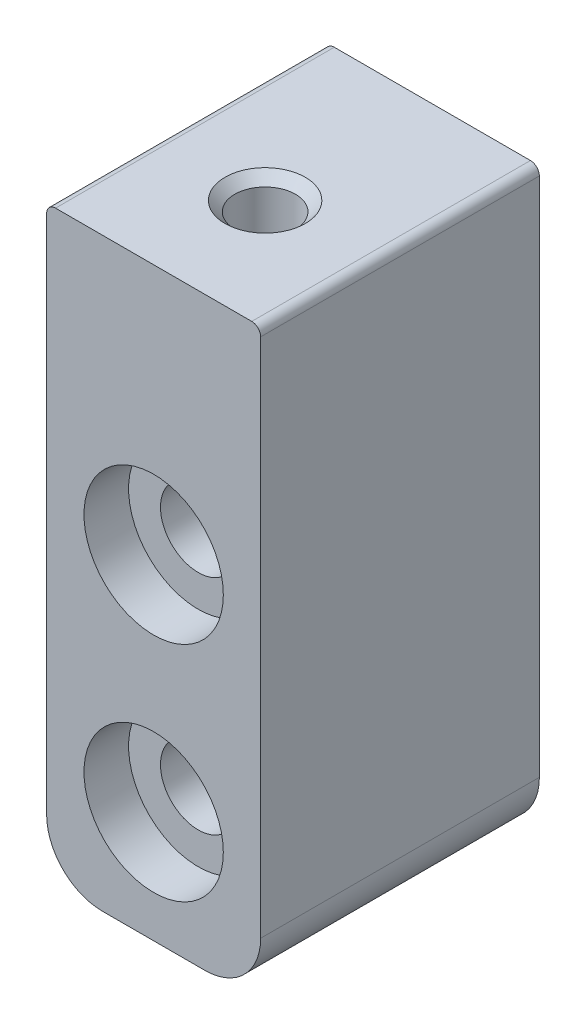
SolidWorks part; units mm, degrees
ref_plane "Front Plane" through (0, 0, 0) normal (0, 0, 1) x (1, 0, 0)
ref_plane "Top Plane" through (0, 0, 0) normal (0, 1, 0) x (1, 0, 0)
ref_plane "Right Plane" through (0, 0, 0) normal (1, 0, 0) x (0, 0, -1)
sketch "Sketch1" plane through (0, 0, 0) normal (1, 0, 0) x (0, 0, -1)
  line L1 (0, 0) -> (-15.875, 0)
  line L2 (0, 0) -> (0, -33.3502)
  line L3 (0, -33.3502) -> (-15.875, -33.3502)
  line L4 (-15.875, 0) -> (-15.875, -33.3502)
  dimension "D1" = 15.875
  dimension "D2" = 33.3502
extrude "Boss-Extrude1" add sketch "Sketch1" along normal mid plane 12.192
hole_wizard "CBORE for #8 Socket Head Cap Screw1" positions "Sketch3" profile "Sketch2" counterbore size "#8" standard "Ansi Inch" end condition through all
sketch "Sketch3" plane through (0, 0, 15.875) normal (0, 0, 1) x (1, 0, 0)
  point P0 (0, -14.3002)
  point P1 (0, -27.0002)
  dimension "D1" = 14.3002
  dimension "D2" = 12.7
sketch "Sketch2" plane through (0, -14.3002, 15.875) normal (1, 0, 0) x (0, -1, 0)
  line L0 (0, 0) -> (0, 15.875)
  line L1 (0, 15.875) -> (2.1526, 15.875)
  line L3 (2.1526, 15.875) -> (2.1527, 2.54)
  line L4 (2.1527, 2.54) -> (3.9688, 2.54)
  line L5 (3.9688, 2.54) -> (3.9687, 0)
  line L7 (3.9687, 0) -> (0, 0)
  line L11 (0, -6.35) -> (0, 107.95) construction
  dimension "Thru Hole Dia." = 4.3053
  dimension "Thru Hole Depth" = 15.875
  dimension "C'Bore Dia." = 7.9375
  dimension "C'Bore Depth" = 2.54
hole_wizard "#8-32 Tapped Hole1" positions "Sketch5" profile "Sketch4" tap size "#8-32" standard "Ansi Inch"
sketch "Sketch5" plane through (0, 0, 0) normal (0, 1, 0) x (-1, 0, 0)
  point P0 (0, 9.525)
  dimension "D1" = 9.525
sketch "Sketch4" plane through (0, 0, 9.525) normal (1, 0, 0) x (0, 0, 1)
  line L0 (0, 0) -> (0, 16.2778)
  line L1 (0, 16.2778) -> (1.7272, 15.24)
  line L2 (1.7272, 15.24) -> (1.7272, 0.5588)
  line L3 (1.7272, 0.5588) -> (2.286, 0)
  line L5 (2.286, 0) -> (0, 0)
  line L6 (-1.7272, 0.5588) -> (-2.286, 0) construction
  line L10 (0, 16.2778) -> (-1.7272, 15.24) construction
  line L11 (0, -6.35) -> (0, 107.95) construction
  dimension "Tap Drill Dia." = 3.4544
  dimension "Tap Drill Depth" = 15.24
  dimension "Near C'Sink Dia." = 4.572
  dimension "Near C'Sink Angle" = 90
  dimension "Drill Angle" = 118
fillet "Fillet1" radius 3.175 2 edges at (-6.096, -33.3502, 7.9375) (6.096, -33.3502, 7.9375)
fillet "Fillet2" radius 0.508 2 edges at (-6.096, 0, 7.9375) (6.096, 0, 7.9375)
